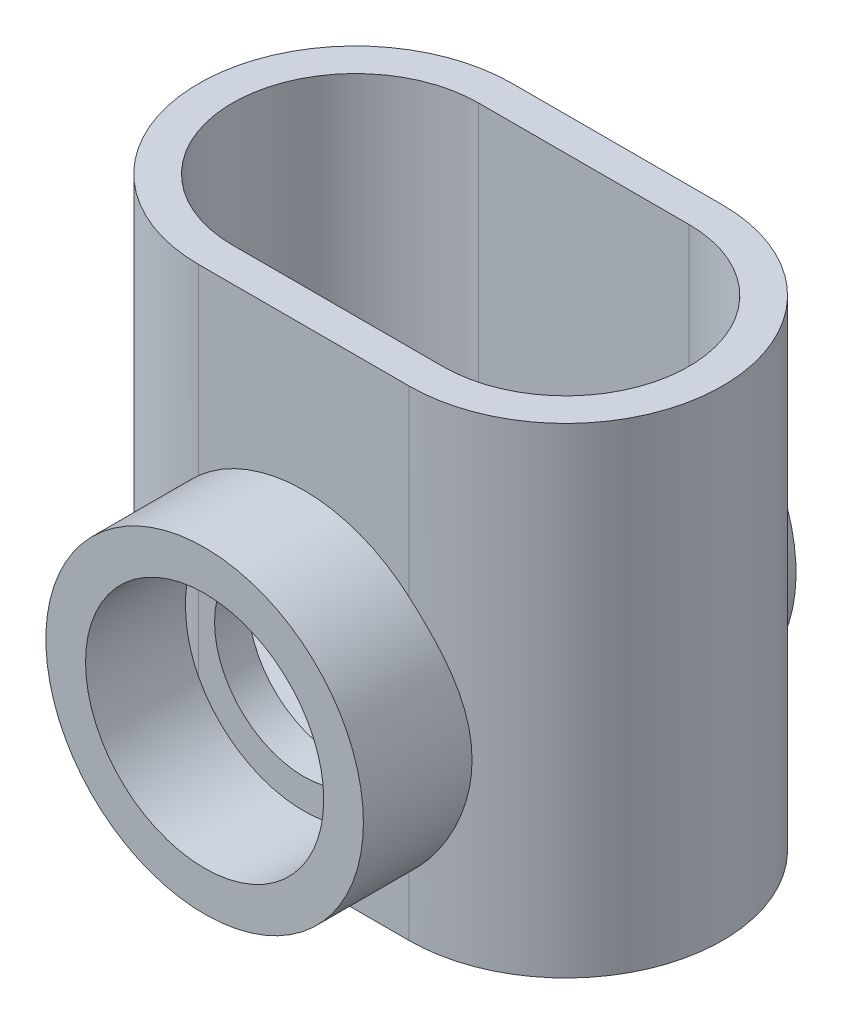
SolidWorks part; units mm, degrees
ref_plane "前基準面" through (0, 0, 0) normal (0, 0, 1) x (1, 0, 0)
ref_plane "上基準面" through (0, 0, 0) normal (0, 1, 0) x (1, 0, 0)
ref_plane "右基準面" through (0, 0, 0) normal (1, 0, 0) x (0, 0, -1)
sketch "草圖1" plane through (0, 0, 0) normal (0, 1, 0) x (1, 0, 0)
  line L0 (0, 0) -> (10.6, 0) construction
  line L3 (0, 7.9) -> (10.6, 7.9)
  line L4 (0, -7.9) -> (10.6, -7.9)
  arc A2 (0, 7.9) -> (0, -7.9) centre (0, 0) ccw
  arc A3 (10.6, -7.9) -> (10.6, 7.9) centre (10.6, 0) ccw
  point P3 (5.3, 0)
  dimension "D1" = 26.4
  dimension "D2" = 15.8
extrude "填料-伸長1" add sketch "草圖1" along normal blind 24.2
shell "薄殼1" thickness 1.7
ref_plane "平面1" through (0, 0, 12.9) normal (0, 0, 1) x (1, 0, 0)
sketch "草圖2" plane through (0, 0, 12.9) normal (0, 0, 1) x (1, 0, 0)
  line L0 (5.3, 24.2) -> (5.3, -2.0344) construction
  line L1 (0, 24.2) -> (10.6, 24.2) construction
  line L2 (10.6, 0) -> (18.5, 0) construction
  circle A0 centre (5.3, 9) radius 8
  circle A1 centre (5.3, 9) radius 6
  dimension "D1" = 16
  dimension "D3" = 12
  dimension "D2" = 9
extrude "填料-伸長2" add sketch "草圖2" against normal up to next
sketch "草圖3" plane through (0, 0, 7.9) normal (0, 0, 1) x (1, 0, 0)
  circle A0 centre (5.3, 9) radius 4.5
  dimension "D1" = 9
extrude "除料-伸長1" cut sketch "草圖3" against normal through all
sketch "草圖4" plane through (0, 0, -7.9) normal (0, 0, -1) x (-1, 0, 0)
  circle A0 centre (-5.3, 9) radius 8
  circle A2 centre (-5.3, 9) radius 4.5 construction
  circle A3 centre (-5.3, 9) radius 4.5
  dimension "D1" = 16
extrude "填料-伸長3" add sketch "草圖4" along normal blind 1
